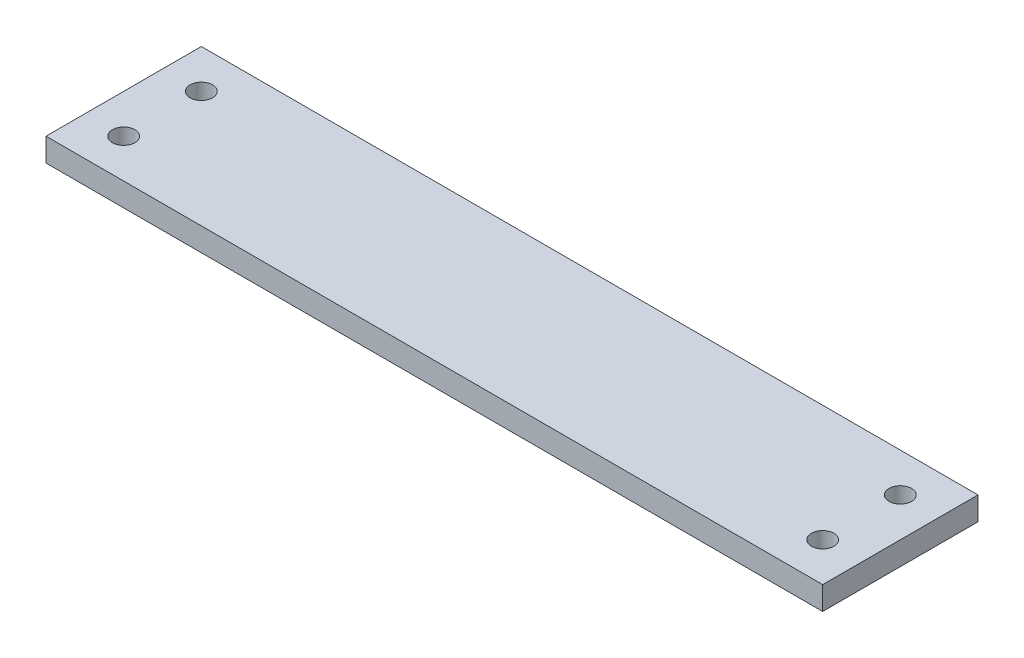
SolidWorks part; units mm, degrees
ref_plane "前视基准面" through (0, 0, 0) normal (0, 0, 1) x (1, 0, 0)
ref_plane "上视基准面" through (0, 0, 0) normal (0, 1, 0) x (1, 0, 0)
ref_plane "右视基准面" through (0, 0, 0) normal (1, 0, 0) x (0, 0, -1)
other "Configuration Table"
sketch "草图1" plane through (0, 0, 0) normal (0, 1, 0) x (1, 0, 0)
  line L1 (0, 0) -> (-100, 0)
  line L2 (0, 0) -> (0, 20)
  line L3 (0, 20) -> (-100, 20)
  line L4 (-100, 0) -> (-100, 20)
  dimension "D1" = 100
  dimension "D2" = 20
extrude "凸台-拉伸1" add sketch "草图1" along normal blind 3
sketch "草图2" plane through (0, 3, 0) normal (0, 1, 0) x (1, 0, 0)
  line L0 (-100, 20) -> (-95, 20) construction
  line L1 (0, 20) -> (-100, 20) construction
  line L2 (-95, 20) -> (-95, 15) construction
  line L3 (-50, 20) -> (-50, -12.4774) construction
  line L4 (-100, 10) -> (-35.9977, 10) construction
  line L5 (-100, 20) -> (-100, 0) construction
  circle A0 centre (-95, 15) radius 1.45
  circle A1 centre (-95, 5) radius 1.45
  circle A2 centre (-5, 5) radius 1.45
  circle A3 centre (-5, 15) radius 1.45
  dimension "D3" = 2.9
  dimension "D1" = 5
  dimension "D2" = 5
extrude "切除-拉伸1" cut sketch "草图2" against normal blind 6
